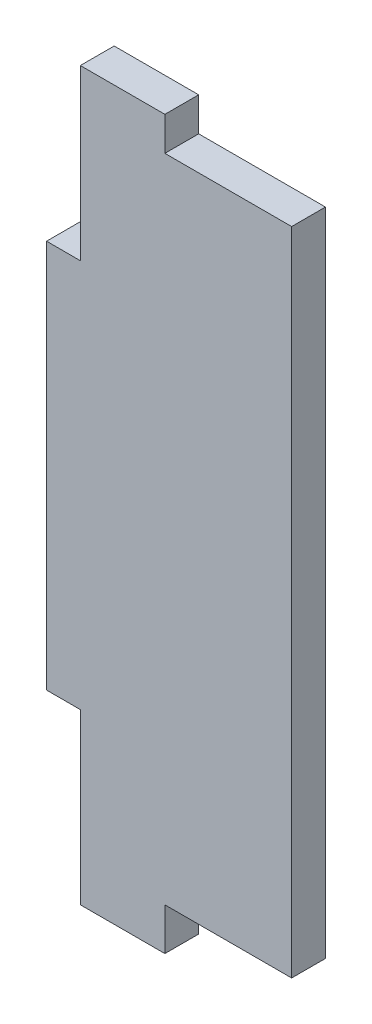
SolidWorks part; units mm, degrees
ref_plane "Front Plane" through (0, 0, 0) normal (0, 0, 1) x (1, 0, 0)
ref_plane "Top Plane" through (0, 0, 0) normal (0, 1, 0) x (1, 0, 0)
ref_plane "Right Plane" through (0, 0, 0) normal (1, 0, 0) x (0, 0, -1)
sketch "Sketch1" plane through (0, 0, 0) normal (0, 0, 1) x (1, 0, 0)
  line L0 (0, 66) -> (0, 86)
  line L1 (0, 0) -> (10, 0)
  line L2 (0, 0) -> (0, 20)
  line L3 (0, 86) -> (10, 86)
  line L4 (25, 5) -> (25, 82)
  line L5 (0, 66) -> (-4, 66)
  line L7 (0, 20) -> (-4, 20)
  line L8 (-4, 66) -> (-4, 20)
  line L10 (10, 86) -> (10, 82)
  line L11 (10, 82) -> (25, 82)
  line L12 (10, 0) -> (10, 5)
  line L13 (10, 5) -> (25, 5)
  dimension "D1" = 10
  dimension "D2" = 82
  dimension "D3" = 4
  dimension "D4" = 20
  dimension "D5" = 20
  dimension "D6" = 4
  dimension "D7" = 5
  dimension "D8" = 10
  dimension "D9" = 25
extrude "Boss-Extrude1" add sketch "Sketch1" along normal blind 4
